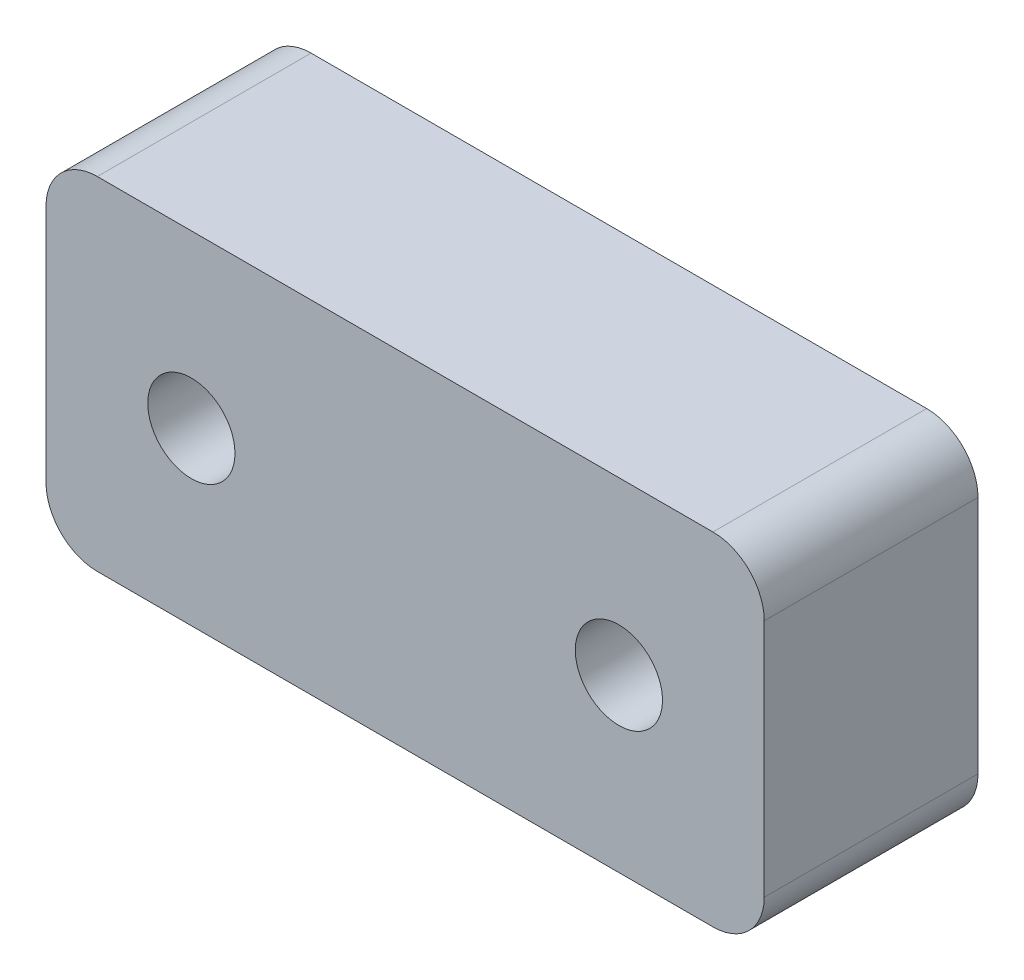
SolidWorks part; units mm, degrees
ref_plane "前视基准面" through (0, 0, 0) normal (0, 0, 1) x (1, 0, 0)
ref_plane "上视基准面" through (0, 0, 0) normal (0, 1, 0) x (1, 0, 0)
ref_plane "右视基准面" through (0, 0, 0) normal (1, 0, 0) x (0, 0, -1)
sketch "草图1" plane through (0, 0, 0) normal (0, 0, 1) x (1, 0, 0)
  line L0 (0, 0) -> (17.9275, 0) construction
  line L1 (0, 0) -> (0, 14.7668) construction
  line L3 (21, -10) -> (-21, -10)
  line L4 (21, -10) -> (21, 10)
  line L5 (21, 10) -> (-21, 10)
  line L6 (-21, -10) -> (-21, 10)
  line L7 (21, -10) -> (-21, 10) construction
  line L8 (21, 10) -> (-21, -10) construction
  point P1 (0, 0)
  dimension "D1" = 20
  dimension "D2" = 42
extrude "凸台-拉伸1" add sketch "草图1" along normal blind 12.5
sketch "草图2" plane through (0, 0, 12.5) normal (0, 0, 1) x (1, 0, 0)
  line L0 (0, 0) -> (23.8966, 0) construction
  line L1 (0, 0) -> (0, 14.2048) construction
  circle A0 centre (-12.5, 0) radius 2.55
  circle A1 centre (12.5, 0) radius 2.55
  dimension "D1" = 5.1
  dimension "D2" = 25
extrude "切除-拉伸1" cut sketch "草图2" against normal through all
fillet "圆角1" radius 3 4 edges at (21, 10, 6.25) (21, -10, 6.25) (-21, 10, 6.25) (-21, -10, 6.25)
